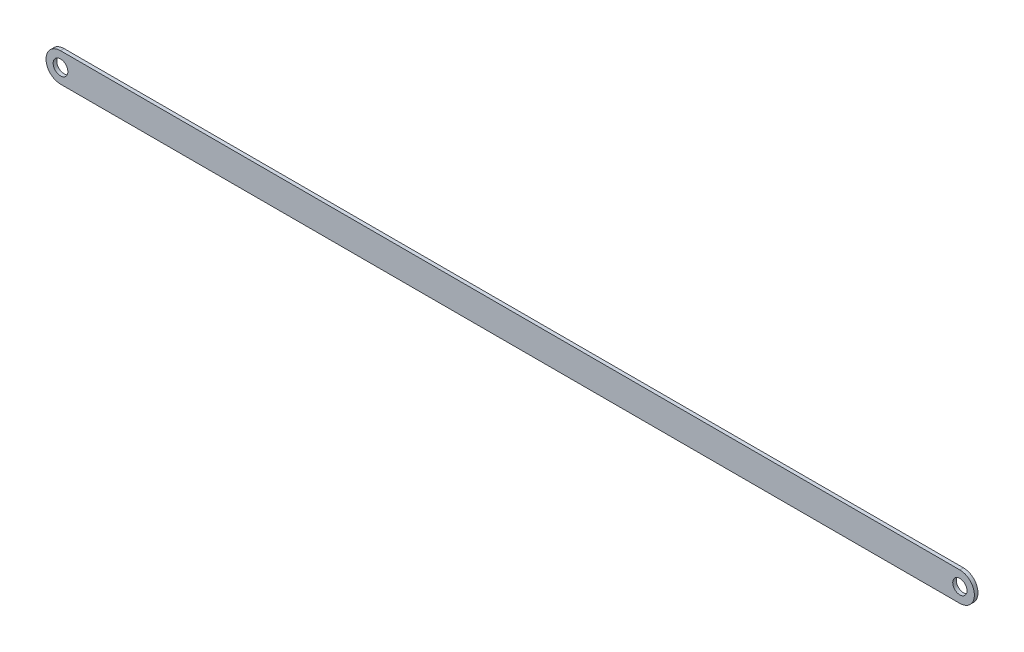
SolidWorks part; units mm, degrees
ref_plane "Front Plane" through (0, 0, 0) normal (0, 0, 1) x (1, 0, 0)
ref_plane "Top Plane" through (0, 0, 0) normal (0, 1, 0) x (1, 0, 0)
ref_plane "Right Plane" through (0, 0, 0) normal (1, 0, 0) x (0, 0, -1)
sketch "Sketch1" plane through (0, 0, 0) normal (0, 0, 1) x (1, 0, 0)
  line L0 (0, 0) -> (787.4, 0) construction
  line L1 (0, 12.7) -> (787.4, 12.7)
  line L2 (0, -12.7) -> (787.4, -12.7)
  arc A0 (0, 12.7) -> (0, -12.7) centre (0, 0) ccw
  arc A1 (787.4, -12.7) -> (787.4, 12.7) centre (787.4, 0) ccw
  circle A2 centre (0, 0) radius 6.4301
  circle A3 centre (787.4, 0) radius 6.2478
  point P3 (393.7, 0)
  dimension "D1" = 25.4
  dimension "D2" = 787.4
extrude "Boss-Extrude1" add sketch "Sketch1" along normal blind 3.175
